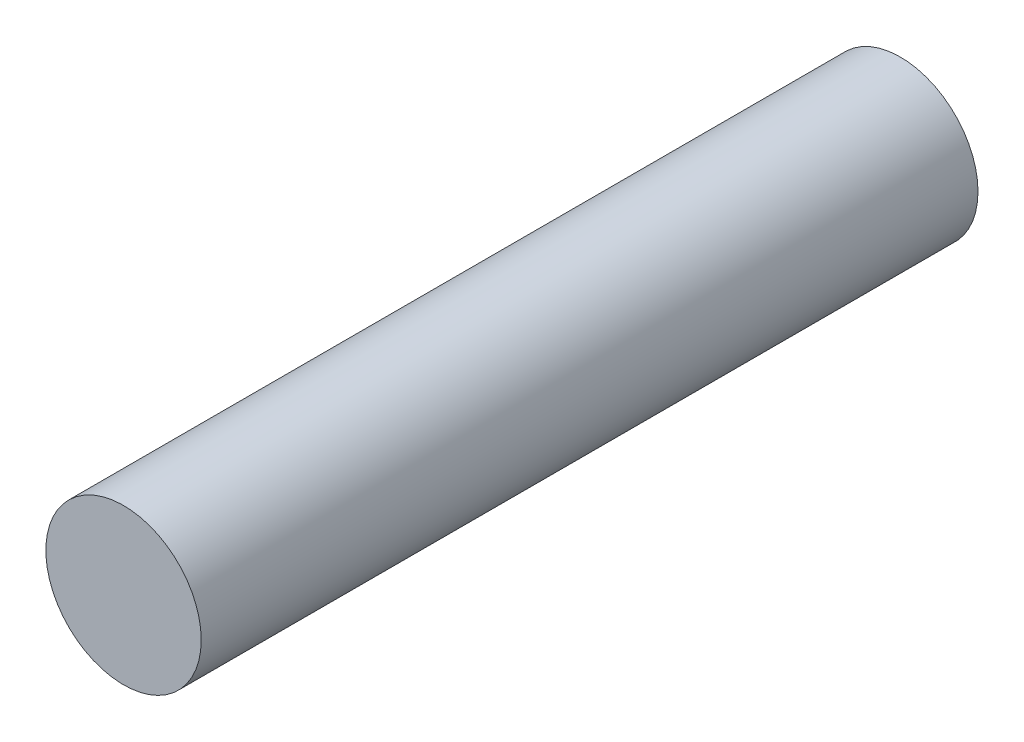
SolidWorks part; units mm, degrees
ref_plane "前视基准面" through (0, 0, 0) normal (0, 0, 1) x (1, 0, 0)
ref_plane "上视基准面" through (0, 0, 0) normal (0, 1, 0) x (1, 0, 0)
ref_plane "右视基准面" through (0, 0, 0) normal (1, 0, 0) x (0, 0, -1)
sketch "草图1" plane through (0, 0, 0) normal (0, 0, 1) x (1, 0, 0)
  circle A0 centre (0, 0) radius 1
  dimension "D1" = 2
extrude "凸台-拉伸1" add sketch "草图1" along normal blind 10
